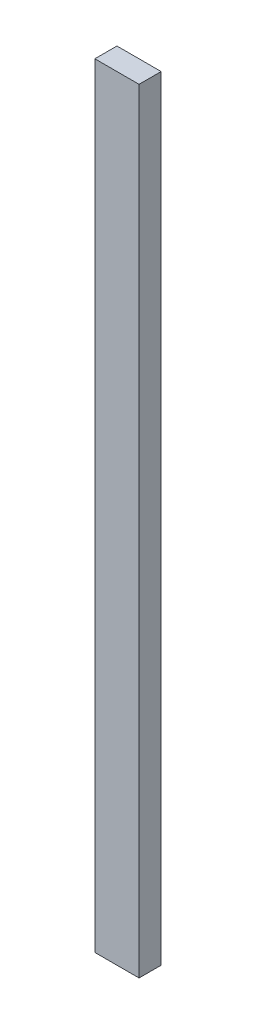
SolidWorks part; units mm, degrees
ref_plane "Front Plane" through (0, 0, 0) normal (0, 0, 1) x (1, 0, 0)
ref_plane "Top Plane" through (0, 0, 0) normal (0, 1, 0) x (1, 0, 0)
ref_plane "Right Plane" through (0, 0, 0) normal (1, 0, 0) x (0, 0, -1)
sketch "Sketch1" plane through (0, 0, 0) normal (0, 1, 0) x (1, 0, 0)
  line L1 (-25.4, 12.7) -> (25.4, 12.7)
  line L2 (-25.4, 12.7) -> (-25.4, -12.7)
  line L3 (-25.4, -12.7) -> (25.4, -12.7)
  line L4 (25.4, 12.7) -> (25.4, -12.7)
  line L5 (-25.4, 12.7) -> (25.4, -12.7) construction
  line L6 (-25.4, -12.7) -> (25.4, 12.7) construction
  point P0 (0, 0)
  dimension "D1" = 50.8
  dimension "D2" = 25.4
extrude "Boss-Extrude2" add sketch "Sketch1" along normal blind 889
